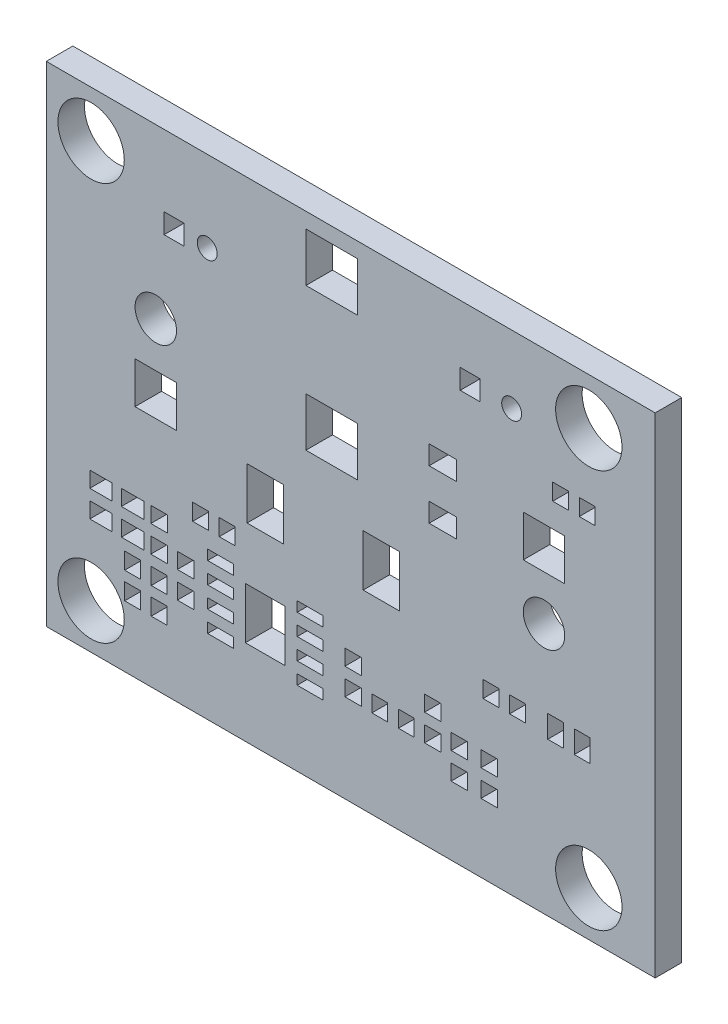
SolidWorks part; units mm, degrees
ref_plane "Plan de face" through (0, 0, 0) normal (0, 0, 1) x (1, 0, 0)
ref_plane "Plan de dessus" through (0, 0, 0) normal (0, 1, 0) x (1, 0, 0)
ref_plane "Plan de droite" through (0, 0, 0) normal (1, 0, 0) x (0, 0, -1)
sketch "Esquisse1" plane through (0, 0, 0) normal (0, 0, 1) x (1, 0, 0)
  line L0 (28.475, -17.475) -> (27.525, -17.475)
  line L1 (27.525, -17.475) -> (27.525, -16.125)
  line L2 (27.525, -16.125) -> (28.475, -16.125)
  line L3 (28.475, -16.125) -> (28.475, -17.475)
  line L4 (30.075, -17.475) -> (29.125, -17.475)
  line L5 (29.125, -17.475) -> (29.125, -16.125)
  line L6 (29.125, -16.125) -> (30.075, -16.125)
  line L7 (30.075, -16.125) -> (30.075, -17.475)
  line L8 (22.025, -8.625) -> (22.025, -9.775)
  line L9 (22.025, -9.775) -> (20.375, -9.775)
  line L10 (20.375, -9.775) -> (20.375, -8.625)
  line L11 (20.375, -8.625) -> (22.025, -8.625)
  line L12 (22.025, -5.625) -> (22.025, -6.775)
  line L13 (22.025, -6.775) -> (20.375, -6.775)
  line L14 (20.375, -6.775) -> (20.375, -5.625)
  line L15 (20.375, -5.625) -> (22.025, -5.625)
  line L16 (22.25, -1.9) -> (22.25, -0.7)
  line L17 (22.25, -0.7) -> (23.45, -0.7)
  line L18 (23.45, -0.7) -> (23.45, -1.9)
  line L19 (23.45, -1.9) -> (22.25, -1.9)
  line L20 (22.25, -1.9) -> (22.25, -0.7)
  line L21 (22.25, -0.7) -> (23.45, -0.7)
  line L22 (23.45, -0.7) -> (23.45, -1.9)
  line L23 (23.45, -1.9) -> (22.25, -1.9)
  line L24 (24.575, -17.3) -> (23.625, -17.3)
  line L25 (23.625, -17.3) -> (23.625, -16.3)
  line L26 (23.625, -16.3) -> (24.575, -16.3)
  line L27 (24.575, -16.3) -> (24.575, -17.3)
  line L28 (26.175, -17.3) -> (25.225, -17.3)
  line L29 (25.225, -17.3) -> (25.225, -16.3)
  line L30 (25.225, -16.3) -> (26.175, -16.3)
  line L31 (26.175, -16.3) -> (26.175, -17.3)
  line L32 (24.5, -21.625) -> (24.5, -22.575)
  line L33 (24.5, -22.575) -> (23.5, -22.575)
  line L34 (23.5, -22.575) -> (23.5, -21.625)
  line L35 (23.5, -21.625) -> (24.5, -21.625)
  line L36 (24.5, -20.025) -> (24.5, -20.975)
  line L37 (24.5, -20.975) -> (23.5, -20.975)
  line L38 (23.5, -20.975) -> (23.5, -20.025)
  line L39 (23.5, -20.025) -> (24.5, -20.025)
  line L40 (21.7, -20.975) -> (21.7, -20.025)
  line L41 (21.7, -20.025) -> (22.7, -20.025)
  line L42 (22.7, -20.025) -> (22.7, -20.975)
  line L43 (22.7, -20.975) -> (21.7, -20.975)
  line L44 (21.7, -22.575) -> (21.7, -21.625)
  line L45 (21.7, -21.625) -> (22.7, -21.625)
  line L46 (22.7, -21.625) -> (22.7, -22.575)
  line L47 (22.7, -22.575) -> (21.7, -22.575)
  line L48 (15.3, -19.775) -> (15.3, -18.825)
  line L49 (15.3, -18.825) -> (16.3, -18.825)
  line L50 (16.3, -18.825) -> (16.3, -19.775)
  line L51 (16.3, -19.775) -> (15.3, -19.775)
  line L52 (15.3, -21.375) -> (15.3, -20.425)
  line L53 (15.3, -20.425) -> (16.3, -20.425)
  line L54 (16.3, -20.425) -> (16.3, -21.375)
  line L55 (16.3, -21.375) -> (15.3, -21.375)
  line L56 (20.1, -19.775) -> (20.1, -18.825)
  line L57 (20.1, -18.825) -> (21.1, -18.825)
  line L58 (21.1, -18.825) -> (21.1, -19.775)
  line L59 (21.1, -19.775) -> (20.1, -19.775)
  line L60 (20.1, -21.375) -> (20.1, -20.425)
  line L61 (20.1, -20.425) -> (21.1, -20.425)
  line L62 (21.1, -20.425) -> (21.1, -21.375)
  line L63 (21.1, -21.375) -> (20.1, -21.375)
  line L64 (17.875, -21.4) -> (16.925, -21.4)
  line L65 (16.925, -21.4) -> (16.925, -20.4)
  line L66 (16.925, -20.4) -> (17.875, -20.4)
  line L67 (17.875, -20.4) -> (17.875, -21.4)
  line L68 (19.475, -21.4) -> (18.525, -21.4)
  line L69 (18.525, -21.4) -> (18.525, -20.4)
  line L70 (18.525, -20.4) -> (19.475, -20.4)
  line L71 (19.475, -20.4) -> (19.475, -21.4)
  line L72 (3.625, -22) -> (4.575, -22)
  line L73 (4.575, -22) -> (4.575, -23)
  line L74 (4.575, -23) -> (3.625, -23)
  line L75 (3.625, -23) -> (3.625, -22)
  line L76 (2.025, -22) -> (2.975, -22)
  line L77 (2.975, -22) -> (2.975, -23)
  line L78 (2.975, -23) -> (2.025, -23)
  line L79 (2.025, -23) -> (2.025, -22)
  line L80 (3.625, -20.4) -> (4.575, -20.4)
  line L81 (4.575, -20.4) -> (4.575, -21.4)
  line L82 (4.575, -21.4) -> (3.625, -21.4)
  line L83 (3.625, -21.4) -> (3.625, -20.4)
  line L84 (2.025, -20.4) -> (2.975, -20.4)
  line L85 (2.975, -20.4) -> (2.975, -21.4)
  line L86 (2.975, -21.4) -> (2.025, -21.4)
  line L87 (2.025, -21.4) -> (2.025, -20.4)
  line L88 (5.2, -19.775) -> (5.2, -18.825)
  line L89 (5.2, -18.825) -> (6.2, -18.825)
  line L90 (6.2, -18.825) -> (6.2, -19.775)
  line L91 (6.2, -19.775) -> (5.2, -19.775)
  line L92 (5.2, -21.375) -> (5.2, -20.425)
  line L93 (5.2, -20.425) -> (6.2, -20.425)
  line L94 (6.2, -20.425) -> (6.2, -21.375)
  line L95 (6.2, -21.375) -> (5.2, -21.375)
  line L96 (29.425, -3.9) -> (30.375, -3.9)
  line L97 (30.375, -3.9) -> (30.375, -4.9)
  line L98 (30.375, -4.9) -> (29.425, -4.9)
  line L99 (29.425, -4.9) -> (29.425, -3.9)
  line L100 (27.825, -3.9) -> (28.775, -3.9)
  line L101 (28.775, -3.9) -> (28.775, -4.9)
  line L102 (28.775, -4.9) -> (27.825, -4.9)
  line L103 (27.825, -4.9) -> (27.825, -3.9)
  line L104 (3.6, -18.175) -> (3.6, -17.225)
  line L105 (3.6, -17.225) -> (4.6, -17.225)
  line L106 (4.6, -17.225) -> (4.6, -18.175)
  line L107 (4.6, -18.175) -> (3.6, -18.175)
  line L108 (3.6, -19.775) -> (3.6, -18.825)
  line L109 (3.6, -18.825) -> (4.6, -18.825)
  line L110 (4.6, -18.825) -> (4.6, -19.775)
  line L111 (4.6, -19.775) -> (3.6, -19.775)
  line L112 (7.725, -15.8) -> (8.675, -15.8)
  line L113 (8.675, -15.8) -> (8.675, -16.8)
  line L114 (8.675, -16.8) -> (7.725, -16.8)
  line L115 (7.725, -16.8) -> (7.725, -15.8)
  line L116 (6.125, -15.8) -> (7.075, -15.8)
  line L117 (7.075, -15.8) -> (7.075, -16.8)
  line L118 (7.075, -16.8) -> (6.125, -16.8)
  line L119 (6.125, -16.8) -> (6.125, -15.8)
  line L120 (16.4, -12.15) -> (18.6, -12.15)
  line L121 (18.6, -12.15) -> (18.6, -15.25)
  line L122 (18.6, -15.25) -> (16.4, -15.25)
  line L123 (16.4, -15.25) -> (16.4, -12.15)
  line L124 (9.4, -12.15) -> (11.6, -12.15)
  line L125 (11.6, -12.15) -> (11.6, -15.25)
  line L126 (11.6, -15.25) -> (9.4, -15.25)
  line L127 (9.4, -15.25) -> (9.4, -12.15)
  line L128 (16.05, -6.725) -> (16.05, -9.675)
  line L129 (16.05, -9.675) -> (12.95, -9.675)
  line L130 (12.95, -9.675) -> (12.95, -6.725)
  line L131 (12.95, -6.725) -> (16.05, -6.725)
  line L132 (16.05, 1.875) -> (16.05, -1.075)
  line L133 (16.05, -1.075) -> (12.95, -1.075)
  line L134 (12.95, -1.075) -> (12.95, 1.875)
  line L135 (12.95, 1.875) -> (16.05, 1.875)
  line L136 (1.825, -18.175) -> (1.825, -17.225)
  line L137 (1.825, -17.225) -> (3.175, -17.225)
  line L138 (3.175, -17.225) -> (3.175, -18.175)
  line L139 (3.175, -18.175) -> (1.825, -18.175)
  line L140 (1.825, -19.775) -> (1.825, -18.825)
  line L141 (1.825, -18.825) -> (3.175, -18.825)
  line L142 (3.175, -18.825) -> (3.175, -19.775)
  line L143 (3.175, -19.775) -> (1.825, -19.775)
  line L144 (-0.075, -18.175) -> (-0.075, -17.225)
  line L145 (-0.075, -17.225) -> (1.275, -17.225)
  line L146 (1.275, -17.225) -> (1.275, -18.175)
  line L147 (1.275, -18.175) -> (-0.075, -18.175)
  line L148 (-0.075, -19.775) -> (-0.075, -18.825)
  line L149 (-0.075, -18.825) -> (1.275, -18.825)
  line L150 (1.275, -18.825) -> (1.275, -19.775)
  line L151 (1.275, -19.775) -> (-0.075, -19.775)
  line L152 (4.4, -2.7) -> (4.4, -1.5)
  line L153 (4.4, -1.5) -> (5.6, -1.5)
  line L154 (5.6, -1.5) -> (5.6, -2.7)
  line L155 (5.6, -2.7) -> (4.4, -2.7)
  line L156 (4.4, -2.7) -> (4.4, -1.5)
  line L157 (4.4, -1.5) -> (5.6, -1.5)
  line L158 (5.6, -1.5) -> (5.6, -2.7)
  line L159 (5.6, -2.7) -> (4.4, -2.7)
  line L160 (26.05, -6.35) -> (28.55, -6.35)
  line L161 (28.55, -6.35) -> (28.55, -8.85)
  line L162 (28.55, -8.85) -> (26.05, -8.85)
  line L163 (26.05, -8.85) -> (26.05, -6.35)
  line L164 (26.05, -6.35) -> (28.55, -6.35)
  line L165 (28.55, -6.35) -> (28.55, -8.85)
  line L166 (28.55, -8.85) -> (26.05, -8.85)
  line L167 (26.05, -8.85) -> (26.05, -6.35)
  line L168 (5.15, -12.55) -> (2.65, -12.55)
  line L169 (2.65, -12.55) -> (2.65, -10.05)
  line L170 (2.65, -10.05) -> (5.15, -10.05)
  line L171 (5.15, -10.05) -> (5.15, -12.55)
  line L172 (5.15, -12.55) -> (2.65, -12.55)
  line L173 (2.65, -12.55) -> (2.65, -10.05)
  line L174 (2.65, -10.05) -> (5.15, -10.05)
  line L175 (5.15, -10.05) -> (5.15, -12.55)
  line L176 (7.025, -18.395) -> (7.025, -17.7951)
  line L177 (7.025, -17.7951) -> (8.5749, -17.7951)
  line L178 (8.5749, -17.7951) -> (8.5749, -18.395)
  line L179 (8.5749, -18.395) -> (7.025, -18.395)
  line L180 (7.025, -19.665) -> (7.025, -19.0651)
  line L181 (7.025, -19.0651) -> (8.5749, -19.0651)
  line L182 (8.5749, -19.0651) -> (8.5749, -19.665)
  line L183 (8.5749, -19.665) -> (7.025, -19.665)
  line L184 (7.025, -20.935) -> (7.025, -20.3351)
  line L185 (7.025, -20.3351) -> (8.5749, -20.3351)
  line L186 (8.5749, -20.3351) -> (8.5749, -20.935)
  line L187 (8.5749, -20.935) -> (7.025, -20.935)
  line L188 (7.025, -22.205) -> (7.025, -21.6051)
  line L189 (7.025, -21.6051) -> (8.5749, -21.6051)
  line L190 (8.5749, -21.6051) -> (8.5749, -22.205)
  line L191 (8.5749, -22.205) -> (7.025, -22.205)
  line L192 (12.425, -22.205) -> (12.425, -21.6051)
  line L193 (12.425, -21.6051) -> (13.9749, -21.6051)
  line L194 (13.9749, -21.6051) -> (13.9749, -22.205)
  line L195 (13.9749, -22.205) -> (12.425, -22.205)
  line L196 (12.425, -20.935) -> (12.425, -20.3351)
  line L197 (12.425, -20.3351) -> (13.9749, -20.3351)
  line L198 (13.9749, -20.3351) -> (13.9749, -20.935)
  line L199 (13.9749, -20.935) -> (12.425, -20.935)
  line L200 (12.425, -19.665) -> (12.425, -19.0651)
  line L201 (12.425, -19.0651) -> (13.9749, -19.0651)
  line L202 (13.9749, -19.0651) -> (13.9749, -19.665)
  line L203 (13.9749, -19.665) -> (12.425, -19.665)
  line L204 (12.425, -18.395) -> (12.425, -17.7951)
  line L205 (12.425, -17.7951) -> (13.9749, -17.7951)
  line L206 (13.9749, -17.7951) -> (13.9749, -18.395)
  line L207 (13.9749, -18.395) -> (12.425, -18.395)
  line L208 (11.7, -21.55) -> (9.3, -21.55)
  line L209 (9.3, -21.55) -> (9.3, -18.45)
  line L210 (9.3, -18.45) -> (11.7, -18.45)
  line L211 (11.7, -18.45) -> (11.7, -21.55)
  line L212 (-2.7, -26.7) -> (-2.7, 2.8)
  line L213 (-2.7, 2.8) -> (34, 2.8)
  line L214 (34, 2.8) -> (34, -26.7)
  line L215 (34, -26.7) -> (-2.7, -26.7)
  circle A0 centre (25.35, -1.3) radius 0.6
  circle A1 centre (25.35, -1.3) radius 0.6
  circle A2 centre (7, -2.1) radius 0.6
  circle A3 centre (7, -2.1) radius 0.6
  circle A4 centre (27.3, -11.56) radius 1.25
  circle A5 centre (27.3, -11.56) radius 1.25
  circle A6 centre (3.9, -7.34) radius 1.25
  circle A7 centre (3.9, -7.34) radius 1.25
  circle A8 centre (30, -24) radius 2
  circle A9 centre (30, -24) radius 2
  circle A10 centre (0, -24) radius 2
  circle A11 centre (0, -24) radius 2
  circle A12 centre (30, 0) radius 2
  circle A13 centre (30, 0) radius 2
  circle A14 centre (0, 0) radius 2
  circle A15 centre (0, 0) radius 2
extrude "Boss.-Extru.1" add sketch "Esquisse1" along normal blind 1.6 contours L215 L214 L213 L212 A14 A12 A10 A8 A6 A4 A2 A0 L2 L3 L0 L1 L6 L7 L4 L5 L10 L11 L8 L9 L14 L15 L12 L13 L18 L19 L16 L17 L26 L27 L24 L25
